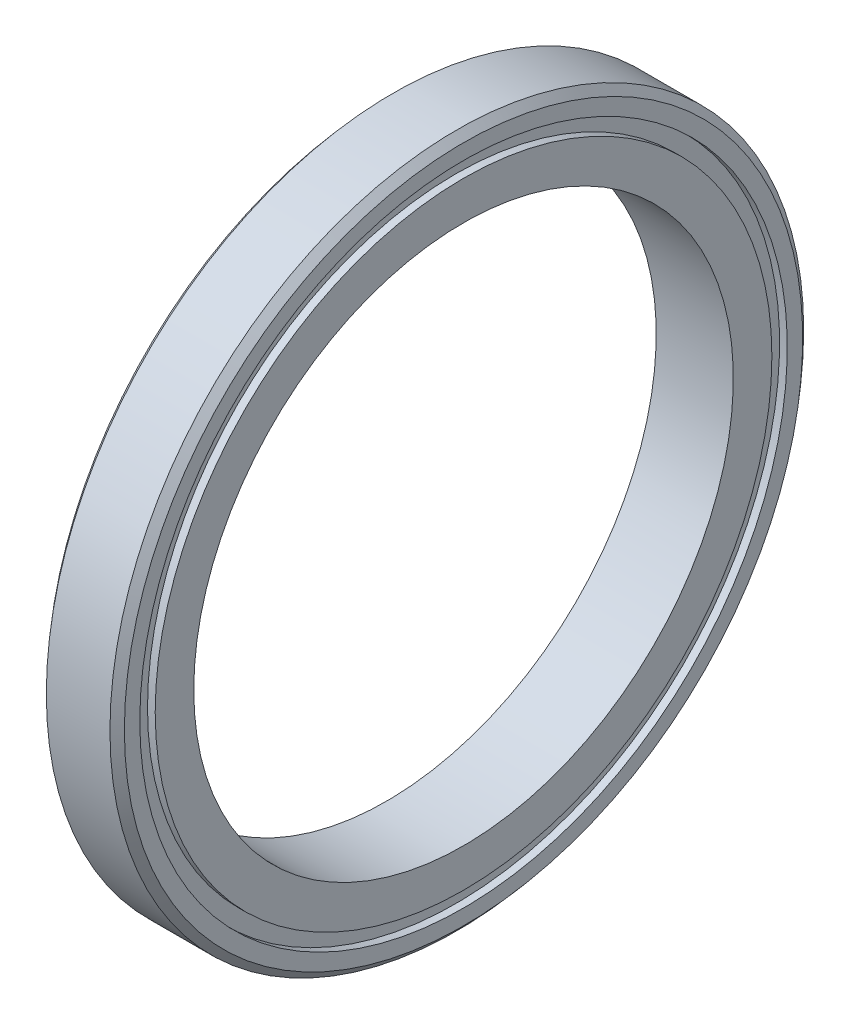
SolidWorks part; units mm, degrees
material "Plain Carbon Steel"
ref_plane "Front Plane" through (0, 0, 0) normal (0, 0, 1) x (1, 0, 0)
ref_plane "Top Plane" through (0, 0, 0) normal (0, 1, 0) x (1, 0, 0)
ref_plane "Right Plane" through (0, 0, 0) normal (1, 0, 0) x (0, 0, -1)
sketch "Sketch1" plane through (0, 0, 0) normal (0, 0, 1) x (1, 0, 0)
  line L0 (0, 0) -> (38.1638, 0) construction
  line L1 (2.8447, 40) -> (1.8447, 40)
  line L2 (-7.1553, 35) -> (2.8447, 35)
  line L3 (-2.1553, 35) -> (-2.1553, 45) construction
  line L4 (1.8447, 40) -> (1.8447, 42)
  line L5 (2.8447, 35) -> (2.8447, 40)
  line L6 (1.8447, 42) -> (2.8447, 42)
  line L7 (2.8447, 42) -> (2.8447, 44)
  line L8 (2.8447, 44) -> (1.9715, 45)
  line L9 (1.9715, 45) -> (-6.2821, 45)
  line L10 (-7.1553, 44) -> (-6.2821, 45)
  line L11 (-7.1553, 42) -> (-7.1553, 44)
  line L12 (-6.1553, 42) -> (-7.1553, 42)
  line L13 (-7.1553, 35) -> (-7.1553, 40)
  line L14 (-6.1553, 40) -> (-6.1553, 42)
  line L15 (-7.1553, 40) -> (-6.1553, 40)
  dimension "D1" = 1
  dimension "D2" = 2
  dimension "D3" = 10
  dimension "D4" = 90
  dimension "D5" = 10
  dimension "D6" = 1
  dimension "D7" = 3
revolve "Revolve1" add sketch "Sketch1" angle 360 about L0
